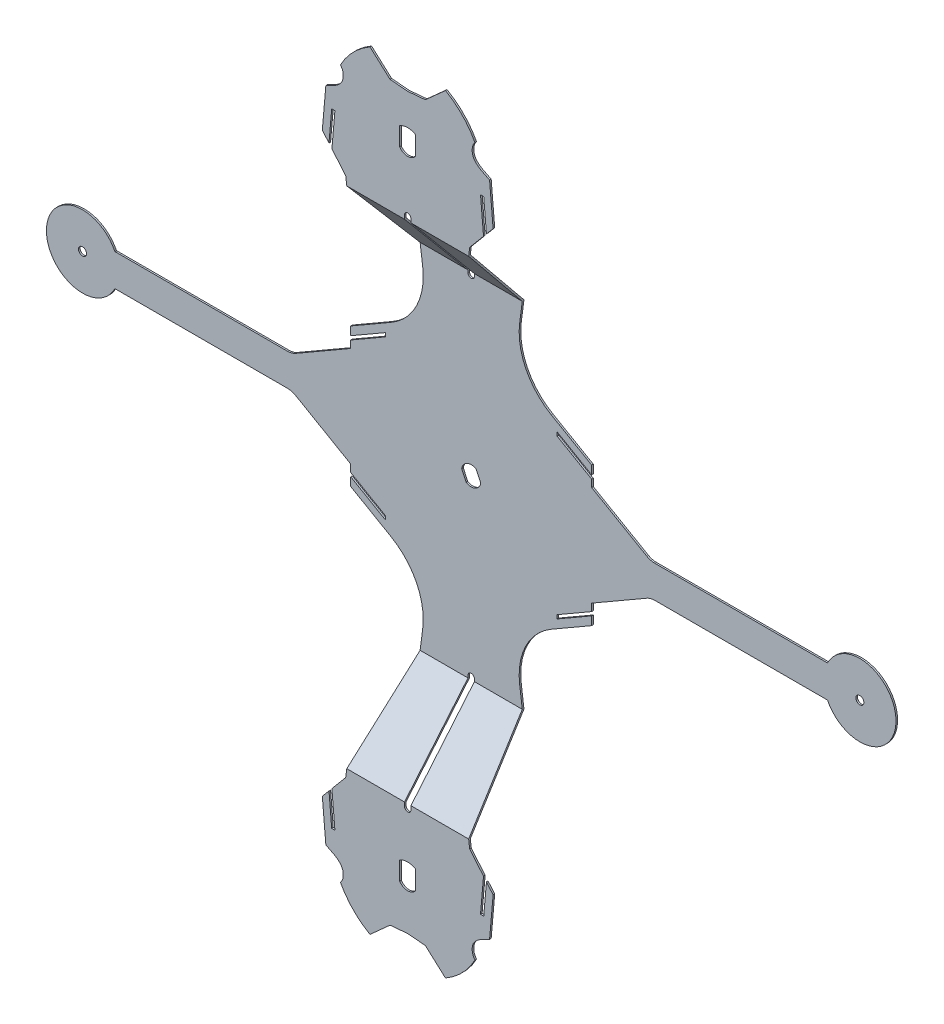
SolidWorks part; units mm, degrees
ref_plane "Alzado" through (0, 0, 0) normal (0, 0, 1) x (1, 0, 0)
ref_plane "Planta" through (0, 0, 0) normal (0, 1, 0) x (1, 0, 0)
ref_plane "Vista lateral" through (0, 0, 0) normal (1, 0, 0) x (0, 0, -1)
sketch "Croquis1" plane through (0, 0, 0) normal (1, 0, 0) x (0, 0, -1)
  line L0 (-18.5, -110) -> (-18.5, 110)
  line L1 (-18.5, 110) -> (-58.0314, 157.1117)
  line L2 (0, 0) -> (-82.8072, 0) construction
  line L3 (-58.0314, 157.1117) -> (-58.0314, 248)
  line L4 (-18.5, -110) -> (-58.0314, -157.1117)
  line L5 (-58.0314, -157.1117) -> (-58.0314, -248)
  line L6 (-57.0314, -157.4757) -> (-57.0314, -248)
  line L7 (-17.5, -110.364) -> (-57.0314, -157.4757)
  line L8 (-17.5, -110.364) -> (-17.5, 110.364)
  line L9 (-17.5, 110.364) -> (-57.0314, 157.4757)
  line L10 (-57.0314, 157.4757) -> (-57.0314, 248)
  line L11 (-58.0314, 248) -> (-57.0314, 248)
  line L12 (-58.0314, -248) -> (-57.0314, -248)
  point P9 (-18.5, 0)
  dimension "D1" = 18.5
  dimension "D2" = 50
  dimension "D3" = 61.5
  dimension "D4" = 110
  dimension "D5" = 496
  dimension "D6" = 1
extrude "Saliente-Extruir1" add sketch "Croquis1" along normal mid plane 542
sketch "Croquis5" plane through (0, 0, 0) normal (0, 0, 1) x (1, 0, 0)
  line L0 (-923.9507, 561.734) -> (-241.388, 573.6482) construction
sketch "Croquis2" plane through (0, 0, 0) normal (0, 0, 1) x (1, 0, 0)
  line L1 (0, 277.0309) -> (0, -277.0309) construction
  line L9 (-300.4496, 0) -> (300.4496, 0) construction
  line L10 (0, 108.5) -> (0, 159.5) construction
  line L11 (-2, 108.5) -> (-2, 159.5)
  line L12 (2, 108.5) -> (2, 159.5)
  line L13 (-30, 152) -> (-47.205, 172.5041) construction
  line L14 (-53.1684, 179.6111) -> (-50.9701, 204.7381)
  line L15 (-23.5, 239.2795) -> (-11, 228.0419)
  line L34 (-11, 228.0419) -> (0, 227.0795)
  line L35 (-49.0231, 174.6708) -> (-47.3316, 194.0041)
  line L36 (-47.3316, 194.0041) -> (-45.324, 194.0041)
  line L37 (-45.324, 194.0041) -> (-47.205, 172.5041)
  line L38 (-49.0231, 174.6708) -> (-53.1684, 179.6111)
  line L45 (-38.6025, 162.2521) -> (-26.75, 71.1584)
  line L79 (0, 86.6025) -> (-75, 43.3013) construction
  line L83 (-75, 43.3013) -> (-75, 38.0358)
  line L84 (-75, -43.3013) -> (0, -86.6025) construction
  line L85 (0, -86.6025) -> (75, -43.3013) construction
  line L86 (75, -43.3013) -> (75, 43.3013) construction
  line L87 (75, 43.3013) -> (0, 86.6025) construction
  line L88 (-38.6025, 162.2521) -> (-47.205, 172.5041)
  line L89 (-75, 38.0358) -> (-53.5, 50.4489)
  line L90 (-53.5, 50.4489) -> (-53.5, 48.1395)
  line L91 (-53.5, 48.1395) -> (-75, 35.7264)
  line L92 (-221.8444, 10) -> (-111.6613, 10)
  line L93 (-221.8444, -10) -> (-75, -10) construction
  line L94 (-75, 31.1664) -> (-111.6613, 10)
  line L95 (-75, 35.7264) -> (-75, -43.3013) construction
  line L96 (-75, 43.3013) -> (-26.75, 71.1584)
  line L97 (-75, 31.1664) -> (-75, 35.7264)
  line L98 (-221.8444, -10) -> (-111.6613, -10)
  line L99 (-75, -31.1664) -> (-111.6613, -10)
  line L100 (-75, -31.1664) -> (-75, -35.7264)
  line L101 (-53.5, -50.4489) -> (-53.5, -48.1395)
  line L102 (-53.5, -48.1395) -> (-75, -35.7264)
  line L103 (-75, -43.3013) -> (-75, -38.0358)
  line L104 (-75, -38.0358) -> (-53.5, -50.4489)
  line L105 (-75, -43.3013) -> (-26.75, -71.1584)
  line L106 (-38.6025, -162.2521) -> (-26.75, -71.1584)
  line L107 (-38.6025, -162.2521) -> (-47.205, -172.5041)
  line L108 (-45.324, -194.0041) -> (-47.205, -172.5041)
  line L109 (-47.3316, -194.0041) -> (-45.324, -194.0041)
  line L110 (-49.0231, -174.6708) -> (-47.3316, -194.0041)
  line L111 (-49.0231, -174.6708) -> (-53.1684, -179.6111)
  line L112 (-53.1684, -179.6111) -> (-50.9701, -204.7381)
  line L113 (-23.5, -239.2795) -> (-11, -228.0419)
  line L114 (-11, -228.0419) -> (0, -227.0795)
  line L115 (30, 152) -> (47.205, 172.5041) construction
  line L116 (11, -228.0419) -> (0, -227.0795)
  line L117 (23.5, -239.2795) -> (11, -228.0419)
  line L118 (53.1684, -179.6111) -> (50.9701, -204.7381)
  line L119 (49.0231, -174.6708) -> (53.1684, -179.6111)
  line L120 (49.0231, -174.6708) -> (47.3316, -194.0041)
  line L121 (47.3316, -194.0041) -> (45.324, -194.0041)
  line L122 (45.324, -194.0041) -> (47.205, -172.5041)
  line L123 (38.6025, -162.2521) -> (47.205, -172.5041)
  line L124 (38.6025, -162.2521) -> (26.75, -71.1584)
  line L125 (75, -43.3013) -> (26.75, -71.1584)
  line L126 (75, -38.0358) -> (53.5, -50.4489)
  line L127 (75, -43.3013) -> (75, -38.0358)
  line L128 (53.5, -48.1395) -> (75, -35.7264)
  line L129 (53.5, -50.4489) -> (53.5, -48.1395)
  line L130 (75, -31.1664) -> (75, -35.7264)
  line L131 (75, -31.1664) -> (111.6613, -10)
  line L132 (221.8444, -10) -> (111.6613, -10)
  line L133 (75, 31.1664) -> (75, 35.7264)
  line L134 (75, 43.3013) -> (26.75, 71.1584)
  line L135 (75, 31.1664) -> (111.6613, 10)
  line L136 (221.8444, 10) -> (111.6613, 10)
  line L137 (53.5, 48.1395) -> (75, 35.7264)
  line L138 (53.5, 50.4489) -> (53.5, 48.1395)
  line L139 (75, 38.0358) -> (53.5, 50.4489)
  line L140 (38.6025, 162.2521) -> (47.205, 172.5041)
  line L141 (75, 43.3013) -> (75, 38.0358)
  line L142 (38.6025, 162.2521) -> (26.75, 71.1584)
  line L143 (49.0231, 174.6708) -> (53.1684, 179.6111)
  line L144 (45.324, 194.0041) -> (47.205, 172.5041)
  line L145 (47.3316, 194.0041) -> (45.324, 194.0041)
  line L146 (49.0231, 174.6708) -> (47.3316, 194.0041)
  line L147 (11, 228.0419) -> (0, 227.0795)
  line L148 (23.5, 239.2795) -> (11, 228.0419)
  line L149 (53.1684, 179.6111) -> (50.9701, 204.7381)
  line L150 (0, -108.5) -> (0, -159.5) construction
  line L151 (-2, -108.5) -> (-2, -159.5)
  line L152 (2, -108.5) -> (2, -159.5)
  line L154 (-300.4496, 277.0309) -> (300.4496, 277.0309)
  line L155 (-300.4496, 277.0309) -> (-300.4496, -277.0309)
  line L156 (-300.4496, -277.0309) -> (300.4496, -277.0309)
  line L157 (300.4496, 277.0309) -> (300.4496, -277.0309)
  line L158 (-300.4496, 277.0309) -> (300.4496, -277.0309) construction
  line L159 (-300.4496, -277.0309) -> (300.4496, 277.0309) construction
  circle A9 centre (0, 0) radius 247.5 construction
  arc A12 (-2, 108.5) -> (2, 108.5) centre (0, 108.5) ccw
  arc A13 (2, 159.5) -> (-2, 159.5) centre (0, 159.5) ccw
  arc A14 (-41.8968, 220.3811) -> (-23.5, 239.2795) centre (0, 198) cw
  circle A15 centre (0, 198) radius 47.5 construction
  circle A16 centre (0, 0) radius 75 construction
  arc A22 (-221.8444, 10) -> (-221.8444, -10) centre (-242, 0) ccw
  arc A23 (-41.8968, -220.3811) -> (-23.5, -239.2795) centre (0, -198) ccw
  arc A24 (41.8968, -220.3811) -> (23.5, -239.2795) centre (0, -198) cw
  arc A25 (221.8444, 10) -> (221.8444, -10) centre (242, 0) cw
  arc A26 (41.8968, 220.3811) -> (23.5, 239.2795) centre (0, 198) ccw
  arc A27 (-2, -108.5) -> (2, -108.5) centre (0, -108.5) cw
  arc A28 (2, -159.5) -> (-2, -159.5) centre (0, -159.5) cw
  spline S0 degree 3 poles (-50.9701, 204.7381) (-47.793, 206.2687) (-40.7871, 209.0246) (-39.8831, 216.4184) (-40.7368, 219.1761) (-41.8968, 220.3811) knots 0 0 0 0 0.610721 0.773573 1 1 1 1
  spline S1 degree 3 poles (-50.9701, -204.7381) (-47.793, -206.2687) (-40.7871, -209.0246) (-39.8831, -216.4184) (-40.7368, -219.1761) (-41.8968, -220.3811) knots 0 0 0 0 0.610721 0.773573 1 1 1 1
  spline S2 degree 3 poles (50.9701, -204.7381) (47.793, -206.2687) (40.7871, -209.0246) (39.8831, -216.4184) (40.7368, -219.1761) (41.8968, -220.3811) knots 0 0 0 0 0.610721 0.773573 1 1 1 1
  spline S3 degree 3 poles (50.9701, 204.7381) (47.793, 206.2687) (40.7871, 209.0246) (39.8831, 216.4184) (40.7368, 219.1761) (41.8968, 220.3811) knots 0 0 0 0 0.610721 0.773573 1 1 1 1
  point P6 (0, 0)
  point P7 (0, 0)
  point P15 (0, 134)
  point P58 (-53.5, 49.2942)
  point P126 (0, -134)
  dimension "D1" = 495
  dimension "D3" = 242
  dimension "D9" = 198
  dimension "D4" = 150
  dimension "D6" = 45
  dimension "D10" = 134
  dimension "D14" = 152
  dimension "D5" = 95
  dimension "D23" = 21.6
  dimension "D24" = 4.56
  dimension "D7" = 51
  dimension "D8" = 4
  dimension "D11" = 30
  dimension "D12" = 2
  dimension "D13" = 50
  dimension "D15" = 25.1271
  dimension "D16" = 5
  dimension "D17" = 179.6111
  dimension "D18" = 5
  dimension "D19" = 11
  dimension "D20" = 23.5
  dimension "D21" = 12.2
  dimension "D22" = 21.5
  dimension "D25" = 2
  dimension "D26" = 20
  dimension "D27" = 4.56
  dimension "D28" = 53.5
  dimension "D29" = 21.5
sketch "Croquis4" plane through (0, 0, 0) normal (0, 0, 1) x (1, 0, 0)
  line L0 (-326.6263, 0) -> (326.6263, 0) construction
  line L1 (0, 278.5393) -> (0, -278.5393) construction
  line L2 (-5, -194.6834) -> (5, -201.3166) construction
  line L3 (-5, 201.3166) -> (5, 201.3166) construction
  line L4 (-5, 201.3166) -> (-5, 194.6834)
  line L5 (-5, 194.6834) -> (5, 194.6834) construction
  line L6 (5, 201.3166) -> (5, 194.6834)
  line L7 (-5, 201.3166) -> (5, 194.6834) construction
  line L8 (-5, 194.6834) -> (5, 201.3166) construction
  line L9 (-5, -201.3166) -> (5, -194.6834) construction
  line L10 (-5, -194.6834) -> (5, -194.6834) construction
  line L11 (-5, -201.3166) -> (5, -201.3166) construction
  line L12 (5, -201.3166) -> (5, -194.6834)
  line L13 (-5, -201.3166) -> (-5, -194.6834)
  line L20 (-5, 201.3166) -> (-5, 206.0777)
  line L21 (5, 201.3166) -> (5, 206.0777)
  line L26 (-5.9332, 0.8928) -> (3.1299, 5.119) construction
  line L27 (-5.9332, 0.8928) -> (-3.1299, -5.119)
  line L28 (3.1299, 5.119) -> (5.9332, -0.8928)
  line L29 (-3.1299, -5.119) -> (5.9332, -0.8928) construction
  line L30 (0, 0) -> (-1.4017, 3.0059) construction
  line L31 (-8.5, 202.2426) -> (-8.5, 193.7574) construction
  line L32 (8.5, 202.2426) -> (8.5, 193.7574) construction
  line L33 (-5, -194.6834) -> (-5, -189.9223)
  line L34 (5, -194.6834) -> (5, -189.9223)
  line L36 (-8.5, -202.2426) -> (-8.5, -193.7574) construction
  line L37 (8.5, -202.2426) -> (8.5, -193.7574) construction
  arc A0 (-5, 194.6834) -> (5, 194.6834) centre (0, 198) ccw
  arc A1 (-3.1299, -5.119) -> (5.9332, -0.8928) centre (0, 0) ccw
  arc A4 (5, 201.3166) -> (-5, 201.3166) centre (0, 198) ccw construction
  arc A5 (5, -201.3166) -> (-5, -201.3166) centre (0, -198) cw
  arc A6 (-5, -194.6834) -> (5, -194.6834) centre (0, -198) cw construction
  circle A7 centre (-242, 0) radius 2.5
  arc A10 (3.1299, 5.119) -> (-5.9332, 0.8928) centre (0, 0) ccw
  circle A11 centre (242, 0) radius 2.5
  arc A12 (5, 206.0777) -> (-5, 206.0777) centre (0, 198) ccw
  arc A14 (8.5, 202.2426) -> (-8.5, 202.2426) centre (0, 198) ccw construction
  arc A15 (-8.5, 193.7574) -> (8.5, 193.7574) centre (0, 198) ccw construction
  arc A16 (-5, -189.9223) -> (5, -189.9223) centre (0, -198) cw
  arc A18 (-8.5, -193.7574) -> (8.5, -193.7574) centre (0, -198) cw construction
  arc A19 (8.5, -202.2426) -> (-8.5, -202.2426) centre (0, -198) cw construction
  point P4 (0, 0)
  point P8 (0, 0)
  dimension "D3" = 242
  dimension "D4" = 10
  dimension "D5" = 12
  dimension "D6" = 12
  dimension "D2" = 5
  dimension "D1" = 198
  dimension "D7" = 3.5
  dimension "D8" = 10
  dimension "D9" = 25
  dimension "D10" = 3.5
extrude "Cortar-Extruir9" cut sketch "Croquis4" against normal through all both and the other way through all
extrude "Cortar-Extruir10" cut sketch "Croquis2" against normal through all both and the other way through all contours L157 L154 L155 L156 S3 L149 L143 L146 L145 L144 L140 L142 L134 L141 L139 L138 L137 L133 L135 L136 A25 L132 L131 L130 L128 L129 L126 L127 L125 L124 L123 L122 L121 L120 L119 L118 S2 A24 L117 L116 L114 L113 A23 S1 L112 L111 L110 L109 L108 L107 | A28 L152 A27 L151 | L12 A13 L11 A12
fillet "Redondeo1" radius 40 4 edges at (26.75, -71.1584, 18) (-26.75, -71.1584, 18) (-26.75, 71.1584, 18) (26.75, 71.1584, 18)
fillet "Redondeo2" radius 10 4 edges at (-111.6613, -10, 18) (-111.6613, 10, 18) (111.6613, -10, 18) (111.6613, 10, 18)
